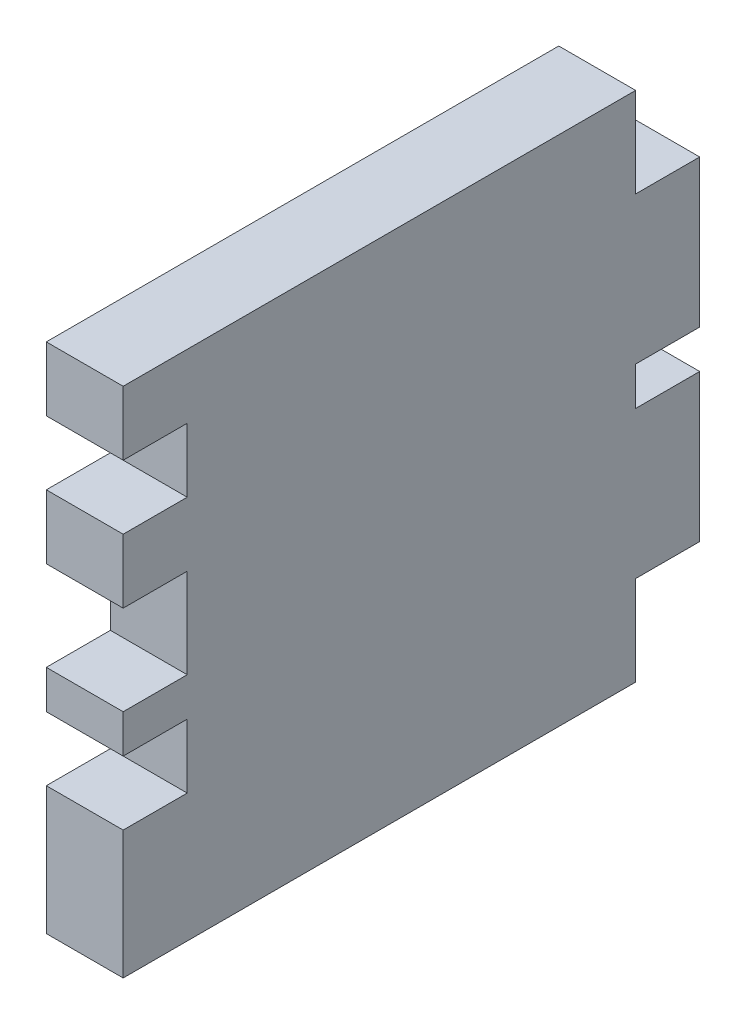
SolidWorks part; units mm, degrees
material "Plain Carbon Steel"
ref_plane "Front" through (0, 0, 0) normal (0, 0, 1) x (1, 0, 0)
ref_plane "Top" through (0, 0, 0) normal (0, 1, 0) x (1, 0, 0)
ref_plane "Right" through (0, 0, 0) normal (1, 0, 0) x (0, 0, -1)
sketch "Sketch1" plane through (0, 0, 0) normal (1, 0, 0) x (0, 0, -1)
  line L1 (-22.4202, 16.7553) -> (22.5798, 16.7553)
  line L2 (-22.4202, 16.7553) -> (-22.4202, -23.2447)
  line L3 (-22.4202, -23.2447) -> (22.5798, -23.2447)
  line L4 (22.5798, 16.7553) -> (22.5798, -23.2447)
  dimension "D1" = 45
  dimension "D2" = 40
extrude "Boss-Extrude1" add sketch "Sketch1" along normal blind 6
sketch "Sketch2" plane through (6, 0, 0) normal (1, 0, 0) x (0, 0, -1)
  line L0 (-22.4202, 16.7553) -> (-22.4202, -23.2447) construction
  line L5 (-22.4202, 11.7553) -> (-17.4202, 11.7553)
  line L6 (-22.4202, 11.7553) -> (-22.4202, 6.7553)
  line L7 (-22.4202, 6.7553) -> (-17.4202, 6.7553)
  line L8 (-17.4202, 11.7553) -> (-17.4202, 6.7553)
  line L9 (22.5798, 16.7553) -> (-22.4202, 16.7553) construction
  line L10 (-22.4202, -23.2447) -> (22.5798, -23.2447) construction
  line L11 (-22.4202, 1.7553) -> (-17.4202, 1.7553)
  line L12 (-22.4202, 1.7553) -> (-22.4202, -5.2447)
  line L13 (-22.4202, -5.2447) -> (-17.4202, -5.2447)
  line L14 (-17.4202, 1.7553) -> (-17.4202, -5.2447)
  line L15 (-22.4202, -8.2447) -> (-17.4202, -8.2447)
  line L16 (-22.4202, -8.2447) -> (-22.4202, -13.2447)
  line L17 (-22.4202, -13.2447) -> (-17.4202, -13.2447)
  line L18 (-17.4202, -8.2447) -> (-17.4202, -13.2447)
  dimension "D1" = 5
  dimension "D2" = 5
  dimension "D3" = 5
  dimension "D4" = 10
  dimension "D5" = 3
  dimension "D6" = 5
  dimension "D7" = 7
extrude "Cut-Extrude1" cut sketch "Sketch2" against normal blind 6 contours L6 L5 L8 L7 | L12 L11 L14 L13 | L16 L15 L18 L17
sketch "Sketch3" plane through (6, 0, 0) normal (1, 0, 0) x (0, 0, -1)
  line L0 (22.5798, -23.2447) -> (22.5798, 16.7553) construction
  line L1 (22.5798, 16.7553) -> (17.5798, 16.7553)
  line L2 (22.5798, 16.7553) -> (22.5798, 9.7553)
  line L3 (22.5798, 9.7553) -> (17.5798, 9.7553)
  line L4 (17.5798, 16.7553) -> (17.5798, 9.7553)
  line L5 (-22.4202, -23.2447) -> (22.5798, -23.2447) construction
  line L6 (17.5798, -1.7447) -> (22.5798, -1.7447)
  line L7 (17.5798, -1.7447) -> (17.5798, -4.7447)
  line L8 (17.5798, -4.7447) -> (22.5798, -4.7447)
  line L9 (22.5798, -1.7447) -> (22.5798, -4.7447)
  line L10 (17.5798, -16.2447) -> (22.5798, -16.2447)
  line L11 (17.5798, -16.2447) -> (17.5798, -23.2447)
  line L12 (17.5798, -23.2447) -> (22.5798, -23.2447)
  line L13 (22.5798, -16.2447) -> (22.5798, -23.2447)
  line L14 (22.5798, 16.7553) -> (-22.4202, 16.7553) construction
  dimension "D1" = 5
  dimension "D2" = 7
  dimension "D3" = 3
  dimension "D4" = 7
  dimension "D5" = 0
  dimension "D6" = 0
  dimension "D7" = 11.5
extrude "Cut-Extrude2" cut sketch "Sketch3" against normal blind 6 contours L2 L1 L4 L3 | L7 L6 L9 L8 | L11 L10 L13 L12
